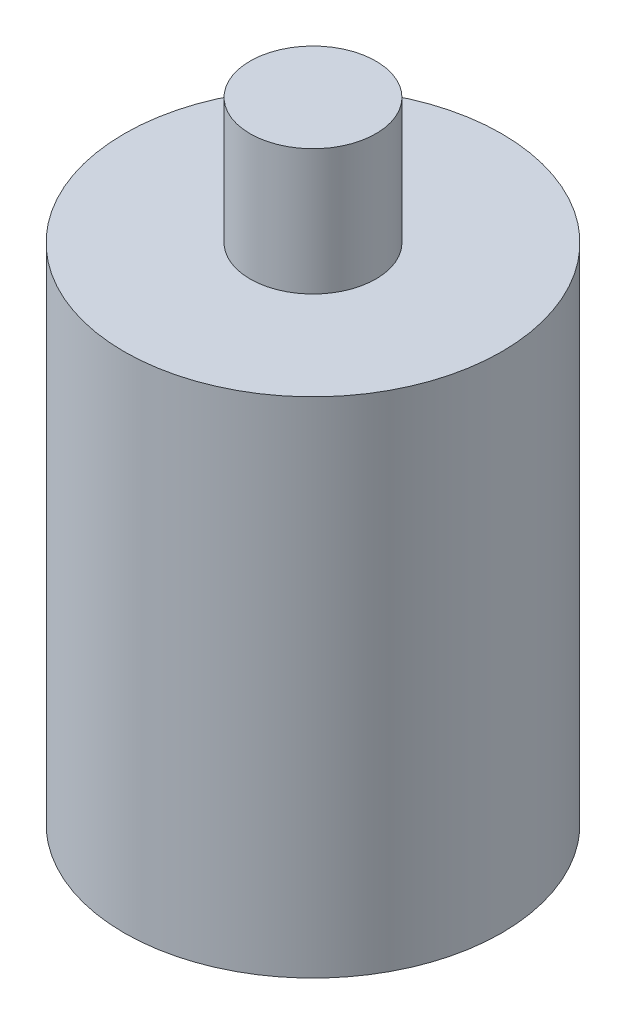
SolidWorks part; units mm, degrees
ref_plane "Front Plane" through (0, 0, 0) normal (0, 0, 1) x (1, 0, 0)
ref_plane "Top Plane" through (0, 0, 0) normal (0, 1, 0) x (1, 0, 0)
ref_plane "Right Plane" through (0, 0, 0) normal (1, 0, 0) x (0, 0, -1)
sketch "Sketch1" plane through (0, 0, 0) normal (0, 1, 0) x (1, 0, 0)
  circle A0 centre (0, 0) radius 38.1
  dimension "D1" = 76.2
extrude "Boss-Extrude1" add sketch "Sketch1" along normal blind 101.6
sketch "Sketch2" plane through (0, 101.6, 0) normal (0, 1, 0) x (1, 0, 0)
  circle A0 centre (0, 0) radius 12.7
  dimension "D1" = 25.4
extrude "Boss-Extrude2" add sketch "Sketch2" along normal blind 25.4
